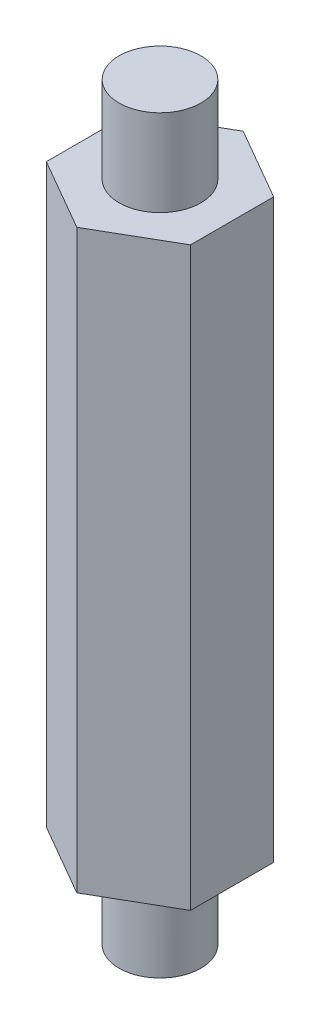
SolidWorks part; units mm, degrees
ref_plane "Front Plane" through (0, 0, 0) normal (0, 0, 1) x (1, 0, 0)
ref_plane "Top Plane" through (0, 0, 0) normal (0, 1, 0) x (1, 0, 0)
ref_plane "Right Plane" through (0, 0, 0) normal (1, 0, 0) x (0, 0, -1)
sketch "Sketch1" plane through (0, 0, 0) normal (0, 1, 0) x (1, 0, 0)
  line L1 (0, 2.8868) -> (-2.5, 1.4434)
  line L2 (-2.5, 1.4434) -> (-2.5, -1.4434)
  line L3 (-2.5, -1.4434) -> (0, -2.8868)
  line L4 (0, -2.8868) -> (2.5, -1.4434)
  line L5 (2.5, -1.4434) -> (2.5, 1.4434)
  line L6 (2.5, 1.4434) -> (0, 2.8868)
  circle A0 centre (0, 0) radius 2.5 construction
  dimension "D1" = 5
extrude "Boss-Extrude1" add sketch "Sketch1" along normal blind 20
sketch "Sketch2" plane through (0, 20, 0) normal (0, 1, 0) x (1, 0, 0)
  circle A0 centre (0, 0) radius 1.42
  dimension "D1" = 2.84
extrude "Boss-Extrude2" add sketch "Sketch2" along normal blind 3
sketch "Sketch3" plane through (0, 0, 0) normal (0, -1, 0) x (-1, 0, 0)
  circle A0 centre (0, 0) radius 1.42
  dimension "D1" = 2.84
extrude "Boss-Extrude3" add sketch "Sketch3" along normal blind 3
